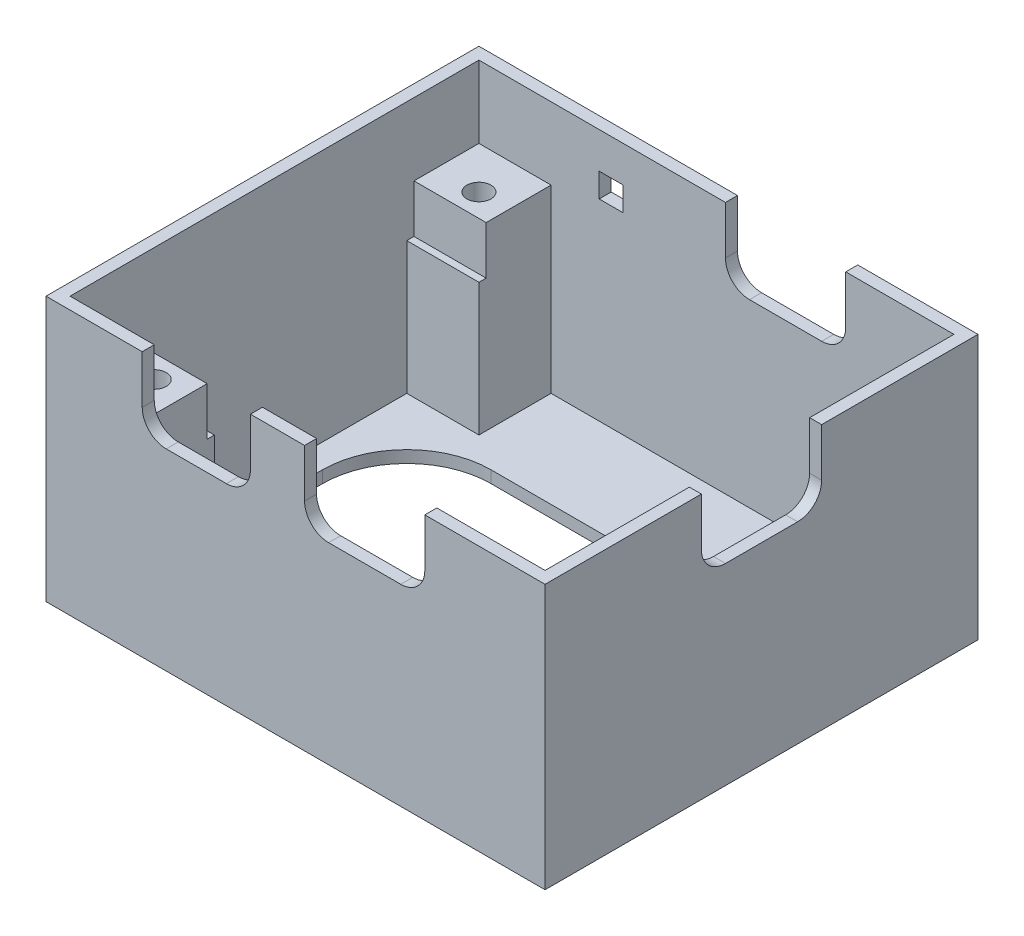
SolidWorks part; units mm, degrees
ref_plane "Front Plane" through (0, 0, 0) normal (0, 0, 1) x (1, 0, 0)
ref_plane "Top Plane" through (0, 0, 0) normal (0, 1, 0) x (1, 0, 0)
ref_plane "Right Plane" through (0, 0, 0) normal (1, 0, 0) x (0, 0, -1)
sketch "Sketch1" plane through (0, 0, 0) normal (0, 1, 0) x (1, 0, 0)
  line L1 (-10.8398, 23.3657) -> (-4.8398, 23.3657)
  line L2 (-10.8398, 23.3657) -> (-10.8398, 17.3657)
  line L5 (-10.8398, 23.3657) -> (-4.8398, 17.3657) construction
  line L6 (-9.8398, 17.3657) -> (-4.8398, 22.3657) construction
  line L7 (22.6602, 23.3657) -> (28.6602, 23.3657)
  line L10 (28.6602, 23.3657) -> (28.6602, 17.3657)
  line L11 (22.6602, 22.3657) -> (27.6602, 17.3657) construction
  line L12 (22.6602, 17.3657) -> (28.6602, 23.3657) construction
  line L14 (-10.8398, -4.6343) -> (-10.8398, -10.6343)
  line L15 (-10.8398, -10.6343) -> (-4.8398, -10.6343)
  line L17 (-9.8398, -4.6343) -> (-4.8398, -9.6343) construction
  line L18 (-10.8398, -10.6343) -> (-4.8398, -4.6343) construction
  line L21 (22.6604, -10.6343) -> (28.6604, -10.6343)
  line L22 (28.6604, -4.6343) -> (28.6604, -10.6343)
  line L23 (22.6604, -4.6343) -> (28.6604, -10.6343) construction
  line L24 (22.6604, -9.6343) -> (27.6604, -4.6343) construction
  line L28 (-4.8398, 23.3657) -> (-4.8398, 17.3657)
  line L31 (-10.8398, 17.3657) -> (-4.8398, 17.3657)
  line L36 (22.6602, 23.3657) -> (22.6602, 17.3657)
  line L39 (22.6602, 17.3657) -> (28.6602, 17.3657)
  line L43 (-10.8398, -4.6343) -> (-4.8398, -4.6343)
  line L48 (-4.8398, -4.6343) -> (-4.8398, -10.6343)
  line L51 (22.6604, -4.6343) -> (28.6604, -4.6343)
  line L56 (22.6604, -4.6343) -> (22.6604, -10.6343)
  circle A0 centre (-7.3398, 19.8657) radius 1
  circle A1 centre (25.1602, 19.8657) radius 1
  circle A2 centre (25.1604, -7.1343) radius 1
  circle A3 centre (-7.3398, -7.1343) radius 1
  dimension "D1" = 2
  dimension "D2" = 2
  dimension "D3" = 2
  dimension "D4" = 2
  dimension "D5" = 27
  dimension "D6" = 27
  dimension "D7" = 32.5
  dimension "D8" = 3.5
  dimension "D9" = 3.5
  dimension "D10" = 2.5
  dimension "D11" = 3.5
  dimension "D12" = 3.5
  dimension "D13" = 2.5
  dimension "D14" = 3.5
  dimension "D15" = 3.5
  dimension "D16" = 2.5
  dimension "D17" = 3.5
  dimension "D18" = 3.5
  dimension "D19" = 2.5
  dimension "D20" = 0
extrude "Boss-Extrude1" add sketch "Sketch1" along normal blind 15
sketch "Sketch2" plane through (0, 0, 0) normal (0, -1, 0) x (1, 0, 0)
  line L1 (-10.8398, 10.6343) -> (28.6602, 10.6343)
  line L2 (-10.8398, 10.6343) -> (-10.8398, -23.3657)
  line L3 (-10.8398, -23.3657) -> (28.6602, -23.3657)
  line L4 (28.6602, 10.6343) -> (28.6602, -23.3657)
extrude "Boss-Extrude2" add sketch "Sketch2" along normal blind 1
sketch "Sketch3" plane through (0, -1, 0) normal (0, -1, 0) x (1, 0, 0)
  line L1 (-10.8398, 10.6343) -> (28.6602, 10.6343)
  line L2 (-11.8398, 9.7302) -> (-11.8398, 11.6343)
  line L3 (-11.8398, 11.6343) -> (29.6602, 11.6343)
  line L4 (29.6602, 9.7302) -> (29.6602, 11.6343)
  line L6 (29.6602, 9.7302) -> (29.6602, -24.3657)
  line L7 (29.6602, -24.3657) -> (28.8037, -24.3657)
  line L8 (28.6602, 10.6343) -> (28.6602, -23.3657)
  line L9 (28.8037, -24.3657) -> (-10.6963, -24.3657)
  line L11 (28.6602, -23.3657) -> (-10.8398, -23.3657)
  line L14 (-11.8398, 9.7302) -> (-11.8398, -24.3657)
  line L15 (-11.8398, -24.3657) -> (-10.6963, -24.3657)
  line L16 (-10.8398, 10.6343) -> (-10.8398, -23.3657)
  dimension "D1" = 1
  dimension "D2" = 1
  dimension "D3" = 1
  dimension "D4" = 1
extrude "Boss-Extrude3" add sketch "Sketch3" against normal blind 22
sketch "Sketch4" plane through (0, 0, 0) normal (0, 1, 0) x (1, 0, 0)
  line L0 (-10.8398, 23.3657) -> (28.6602, 23.3657) construction
  line L1 (-8.8398, 15.3657) -> (28.6602, 15.3657)
  line L2 (-8.8398, 15.3657) -> (-8.8398, -2.6343)
  line L3 (-8.8398, -2.6343) -> (28.6602, -2.6343)
  line L4 (28.6602, 15.3657) -> (28.6602, -2.6343)
  line L5 (22.6604, -10.6343) -> (-4.8398, -10.6343) construction
  line L6 (28.6602, 17.3657) -> (28.6602, -4.6343) construction
  line L7 (-10.8398, -4.6343) -> (-10.8398, 17.3657) construction
  dimension "D1" = 8
  dimension "D2" = 8
  dimension "D3" = 0
  dimension "D4" = 2
extrude "Cut-Extrude1" cut sketch "Sketch4" against normal blind 22
fillet "Fillet1" radius 7 4 edges at (-8.8398, -0.5, -15.3657) (-8.8398, -0.5, 2.6343) (28.6602, -0.5, -15.3657) (28.6602, -0.5, 2.6343)
sketch "Sketch7" plane through (0, 15, 0) normal (0, 1, 0) x (1, 0, 0)
  line L0 (-10.8398, -10.6343) -> (-10.8398, 23.3657) construction
  line L1 (-4.8398, 17.3657) -> (-10.8398, 17.3657)
  line L2 (-4.8398, 17.3657) -> (-4.8398, 17.9657)
  line L3 (-4.8398, 17.9657) -> (-10.8398, 17.9657)
  line L4 (-10.8398, 17.3657) -> (-10.8398, 17.9657)
  line L5 (-10.8398, -4.6343) -> (-10.8398, -10.6343) construction
  line L6 (-4.8398, -4.6343) -> (-10.8398, -4.6343)
  line L7 (-4.8398, -4.6343) -> (-4.8398, -5.2343)
  line L8 (-4.8398, -5.2343) -> (-10.8398, -5.2343)
  line L9 (-10.8398, -4.6343) -> (-10.8398, -5.2343)
  dimension "D1" = 0.6
  dimension "D2" = 0.6
extrude "Cut-Extrude2" cut sketch "Sketch7" against normal blind 4
sketch "Sketch8" plane through (28.6602, 0, 0) normal (-1, 0, 0) x (0, 0, 1)
  line L0 (-23.3657, 21) -> (10.6343, 21) construction
  line L1 (-11.3657, 15) -> (-1.3657, 15)
  line L2 (-11.3657, 15) -> (-11.3657, 21)
  line L3 (-11.3657, 21) -> (-1.3657, 21)
  line L4 (-1.3657, 15) -> (-1.3657, 21)
  line L6 (-17.3657, 15) -> (-17.3657, 0) construction
  line L7 (4.6343, 0) -> (4.6343, 15) construction
  dimension "D1" = 6
  dimension "D2" = 6
extrude "Cut-Extrude3" cut sketch "Sketch8" against normal blind 4
fillet "Fillet2" radius 2 2 edges at (29.1602, 15, -1.3657) (29.1602, 15, -11.3657)
sketch "Sketch9" plane through (0, 0, 10.6343) normal (0, 0, -1) x (-1, 0, 0)
  line L0 (-28.6602, 21) -> (10.8398, 21) construction
  line L1 (-19.6604, 15) -> (-9.6604, 15)
  line L2 (-19.6604, 15) -> (-19.6604, 21)
  line L3 (-19.6604, 21) -> (-9.6604, 21)
  line L4 (-9.6604, 15) -> (-9.6604, 21)
  line L5 (-22.6604, 15) -> (-22.6604, 0) construction
  line L6 (-5.1602, 15) -> (3.8398, 15)
  line L7 (-5.1602, 15) -> (-5.1602, 21)
  line L8 (-5.1602, 21) -> (3.8398, 21)
  line L9 (3.8398, 15) -> (3.8398, 21)
  line L10 (4.8398, 15) -> (4.8398, 0) construction
  dimension "D1" = 3
  dimension "D2" = 10
  dimension "D3" = 1
  dimension "D4" = 9
extrude "Cut-Extrude4" cut sketch "Sketch9" against normal blind 4
fillet "Fillet3" radius 2 4 edges at (5.1602, 15, 11.1343) (-3.8398, 15, 11.1343) (9.6604, 15, 11.1343) (19.6604, 15, 11.1343)
sketch "Sketch10" plane through (0, 0, -23.3657) normal (0, 0, 1) x (1, 0, 0)
  line L0 (-10.8398, 21) -> (28.6602, 21) construction
  line L1 (19.6602, 15) -> (9.6602, 15)
  line L2 (19.6602, 15) -> (19.6602, 21)
  line L3 (19.6602, 21) -> (9.6602, 21)
  line L4 (9.6602, 15) -> (9.6602, 21)
  line L5 (22.6602, 15) -> (22.6602, 0) construction
  dimension "D1" = 3
  dimension "D2" = 10
extrude "Cut-Extrude5" cut sketch "Sketch10" against normal blind 4
fillet "Fillet4" radius 2 2 edges at (19.6602, 15, -23.8657) (9.6602, 15, -23.8657)
sketch "Sketch11" plane through (0, 0, -23.3657) normal (0, 0, 1) x (1, 0, 0)
  line L0 (-4.8398, 15) -> (-10.8398, 15) construction
  line L1 (-0.8398, 18) -> (1.1602, 18)
  line L2 (-0.8398, 18) -> (-0.8398, 16)
  line L3 (-0.8398, 16) -> (1.1602, 16)
  line L4 (1.1602, 18) -> (1.1602, 16)
  line L5 (-4.8398, 15) -> (-4.8398, 0) construction
  dimension "D1" = 1
  dimension "D2" = 2
  dimension "D3" = 2
  dimension "D4" = 4
extrude "Cut-Extrude6" cut sketch "Sketch11" against normal blind 4
